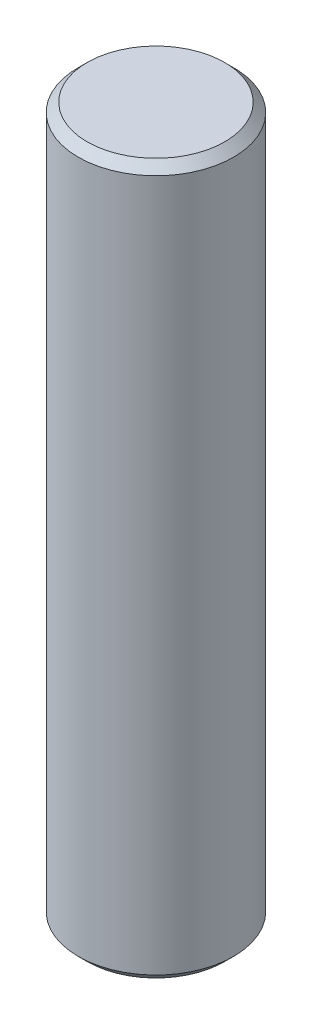
SolidWorks part; units mm, degrees
ref_plane "前视基准面" through (0, 0, 0) normal (0, 0, 1) x (1, 0, 0)
ref_plane "上视基准面" through (0, 0, 0) normal (0, 1, 0) x (1, 0, 0)
ref_plane "右视基准面" through (0, 0, 0) normal (1, 0, 0) x (0, 0, -1)
other "Configuration Table"
sketch "草图1" plane through (0, 0, 0) normal (0, 1, 0) x (1, 0, 0)
  circle A0 centre (0, 0) radius 1.75
  dimension "D1" = 3.5
extrude "凸台-拉伸1" add sketch "草图1" along normal blind 16
chamfer "倒角1" distance 0.2 angle 45 2 edges at (0, 0, 1.75) (0, 16, 1.75)
